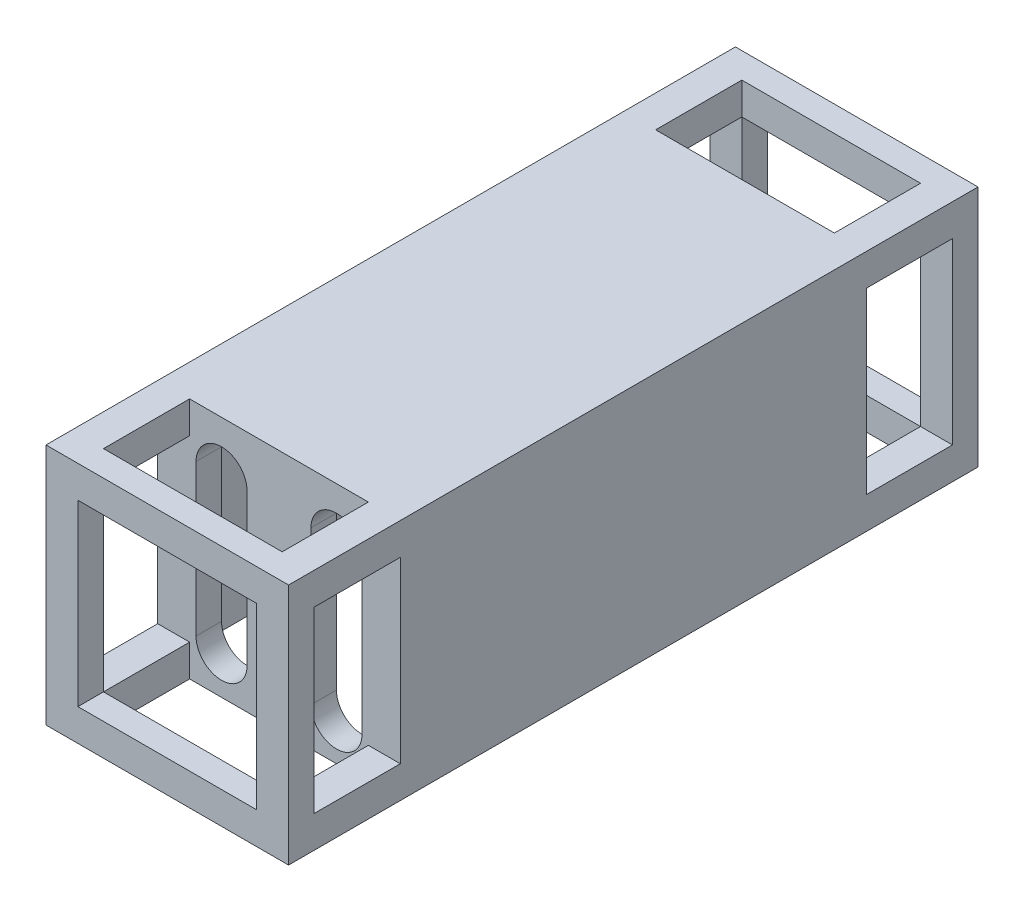
SolidWorks part; units mm, degrees
ref_plane "Plano frontal" through (0, 0, 0) normal (0, 0, 1) x (1, 0, 0)
ref_plane "Plano superior" through (0, 0, 0) normal (0, 1, 0) x (1, 0, 0)
ref_plane "Plano direito" through (0, 0, 0) normal (1, 0, 0) x (0, 0, -1)
sketch "Esboço1" plane through (0, 0, 0) normal (0, 0, 1) x (1, 0, 0)
  line L0 (-9, 9) -> (-9, 27) construction
  line L1 (19, 0) -> (-19, 0)
  line L2 (19, 0) -> (19, 38)
  line L3 (19, 38) -> (-19, 38)
  line L4 (-19, 0) -> (-19, 38)
  line L5 (0, 9) -> (0, 27) construction
  line L6 (0, 38) -> (0, 0) construction
  line L7 (-9, 27) -> (9, 27) construction
  line L8 (9, 27) -> (9, 9) construction
  line L9 (9, 9) -> (0, 9) construction
  line L10 (-9, 36) -> (9, 36)
  line L11 (18, 27) -> (18, 0)
  line L12 (-18, 9) -> (-18, 27)
  line L13 (-18, 9) -> (-18, 0)
  arc A0 (-9, 36) -> (-18, 27) centre (-9, 27) ccw
  arc A1 (18, 27) -> (9, 36) centre (9, 27) ccw
  point P0 (0, 0)
  dimension "D3" = 18
  dimension "D4" = 18
  dimension "D1" = 38
extrude "Ressalto-extrusão1" add sketch "Esboço1" along normal blind 65 contours A1 L11 L1 L2 L3 L4 L13 L12 A0 L10
sketch "Esboço2" plane through (0, 0, 0) normal (0, 0, -1) x (-1, 0, 0)
  line L0 (-9, 30) -> (-9, 6) construction
  line L1 (-19, 38) -> (19, 38)
  line L2 (-19, 38) -> (-19, 0)
  line L3 (-19, 0) -> (19, 0)
  line L4 (19, 38) -> (19, 0)
  line L5 (-5, 30) -> (-5, 6)
  line L6 (-13, 30) -> (-13, 6)
  line L7 (9, 30) -> (9, 6.321) construction
  line L8 (13, 30) -> (13, 6.321)
  line L9 (5, 30) -> (5, 6.321)
  line L10 (-18, 27) -> (-18, 0) construction
  line L11 (9, 36) -> (-9, 36) construction
  arc A0 (-5, 30) -> (-13, 30) centre (-9, 30) ccw
  arc A1 (-13, 6) -> (-5, 6) centre (-9, 6) ccw
  arc A2 (13, 30) -> (5, 30) centre (9, 30) ccw
  arc A3 (5, 6.321) -> (13, 6.321) centre (9, 6.321) ccw
  point P8 (-9, 18)
  point P13 (9, 18.1605)
  dimension "D1" = 18
  dimension "D2" = 9
  dimension "D3" = 6
  dimension "D4" = 6.321
  dimension "D5" = 6
  dimension "D6" = 6
  dimension "D7" = 8
  dimension "D8" = 8
extrude "Ressalto-extrusão2" add sketch "Esboço2" along normal blind 4
ref_plane "Plano1" through (0, 0, 32.5) normal (0, 0, 1) x (1, 0, 0)
sketch "Esboço4" plane through (0, 0, -4) normal (0, 0, -1) x (-1, 0, 0)
  line L0 (-19, 38) -> (-19, 0) construction
  line L1 (19, 38) -> (14, 38)
  line L2 (19, 38) -> (19, 33)
  line L3 (19, 33) -> (14, 33)
  line L4 (14, 38) -> (14, 33)
  line L5 (19, 0) -> (14, 0)
  line L6 (19, 0) -> (19, 5)
  line L7 (19, 5) -> (14, 5)
  line L8 (14, 0) -> (14, 5)
  line L9 (-19, 38) -> (-14, 38)
  line L10 (-19, 38) -> (-19, 33)
  line L11 (-19, 33) -> (-14, 33)
  line L12 (-14, 38) -> (-14, 33)
  line L14 (-19, 0) -> (-14, 0)
  line L15 (-19, 0) -> (-19, 5)
  line L16 (-19, 5) -> (-14, 5)
  line L17 (-14, 0) -> (-14, 5)
  dimension "D1" = 5
extrude "Ressalto-extrusão3" add sketch "Esboço4" along normal blind 13.5
sketch "Esboço5" plane through (0, 0, -17.5) normal (0, 0, -1) x (-1, 0, 0)
  line L1 (19, 38) -> (-19, 38)
  line L2 (19, 38) -> (19, 0)
  line L3 (19, 0) -> (-19, 0)
  line L4 (-19, 38) -> (-19, 0)
  line L5 (-14, 33) -> (14, 33)
  line L6 (-14, 33) -> (-14, 5)
  line L7 (-14, 5) -> (14, 5)
  line L8 (14, 33) -> (14, 5)
extrude "Ressalto-extrusão4" add sketch "Esboço5" along normal blind 4
mirror "Espelhar1" about plane through (0, 0, 32.5) normal (0, 0, 1) of "Ressalto-extrusão4", "Ressalto-extrusão3", "Ressalto-extrusão2"
